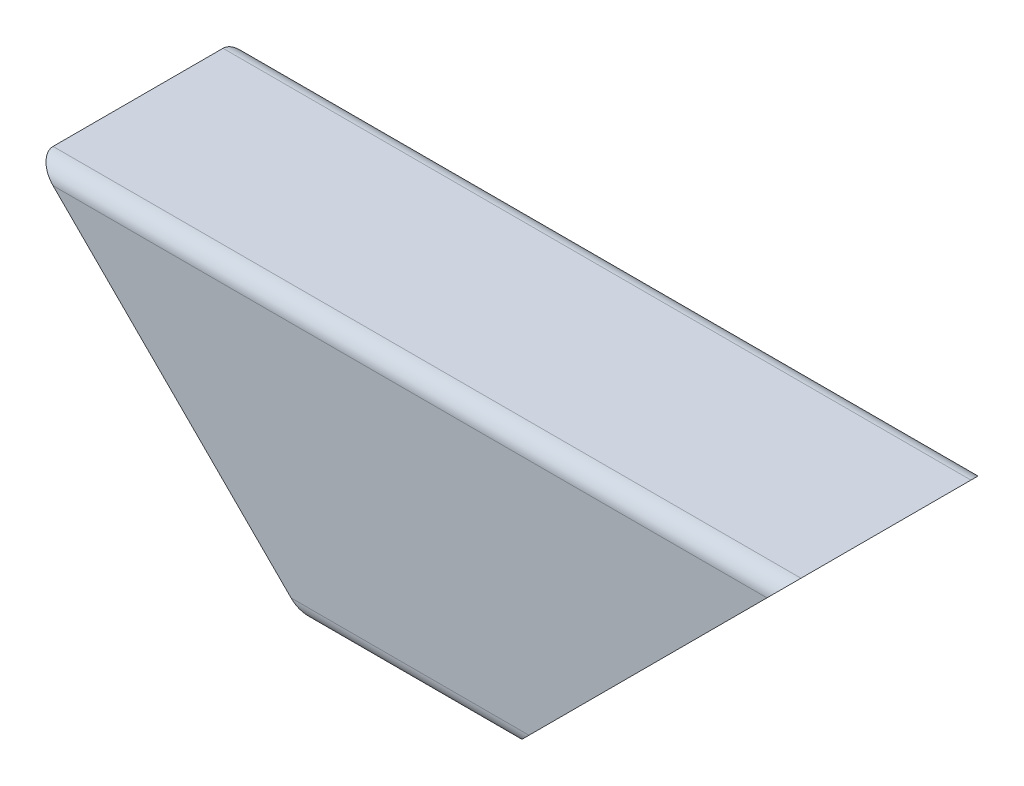
SolidWorks part; units mm, degrees
material "Plain Carbon Steel"
ref_plane "Front Plane" through (0, 0, 0) normal (0, 0, 1) x (1, 0, 0)
ref_plane "Top Plane" through (0, 0, 0) normal (0, 1, 0) x (1, 0, 0)
ref_plane "Right Plane" through (0, 0, 0) normal (1, 0, 0) x (0, 0, -1)
sketch "Sketch1" plane through (0, 0, 0) normal (1, 0, 0) x (0, 0, -1)
  line L1 (-71.6855, -13.3442) -> (-39.9355, -13.3442)
  line L2 (-74.8605, -10.1692) -> (-74.8605, 34.2808)
  line L3 (-71.6855, 37.4558) -> (-39.9355, 37.4558)
  line L4 (-36.7605, -10.1692) -> (-36.7605, 34.2808)
  arc A0 (-74.8605, 34.2808) -> (-71.6855, 37.4558) centre (-71.6855, 34.2808) cw
  arc A1 (-74.8605, -10.1692) -> (-71.6855, -13.3442) centre (-71.6855, -10.1692) ccw
  arc A2 (-39.9355, -13.3442) -> (-36.7605, -10.1692) centre (-39.9355, -10.1692) ccw
  arc A3 (-36.7605, 34.2808) -> (-39.9355, 37.4558) centre (-39.9355, 34.2808) ccw
  point P6 (-74.8605, 37.4558)
  point P11 (-36.7605, -13.3442)
  point P14 (-36.7605, 37.4558)
  dimension "D3" = 3.175
  dimension "D1" = 50.8
  dimension "D2" = 38.1
extrude "Extrude-Thin2" add sketch "Sketch1" along normal blind 139.7 thin thin type one direction reverse wall 1.651
sketch "Sketch3" plane through (0, 0, 74.8605) normal (0, 0, 1) x (1, 0, 0)
  line L0 (0, 37.4558) -> (0, -38.7442)
  line L1 (0, -38.7442) -> (76.2, -38.7442)
  line L2 (76.2, -38.7442) -> (0, 37.4558)
  line L3 (139.7, 37.4558) -> (81.28, -20.9642)
  line L4 (81.28, -20.9642) -> (139.7, -20.9642)
  line L5 (139.7, -20.9642) -> (139.7, 37.4558)
  dimension "D1" = 76.2
  dimension "D2" = 76.2
  dimension "D3" = 58.42
  dimension "D4" = 58.42
extrude "Cut-Extrude1" cut sketch "Sketch3" against normal through all
sketch "Sketch4" plane through (0, 0, 74.8605) normal (0, 0, 1) x (1, 0, 0)
  circle A0 centre (69.85, 18.4058) radius 4.7625
  dimension "D1" = 9.525
  dimension "D2" = 19.05
  dimension "D3" = 69.85
sketch "Sketch5" plane through (0, 0, 74.8605) normal (0, 0, 1) x (1, 0, 0)
  circle A0 centre (69.85, 18.4058) radius 4.7625
